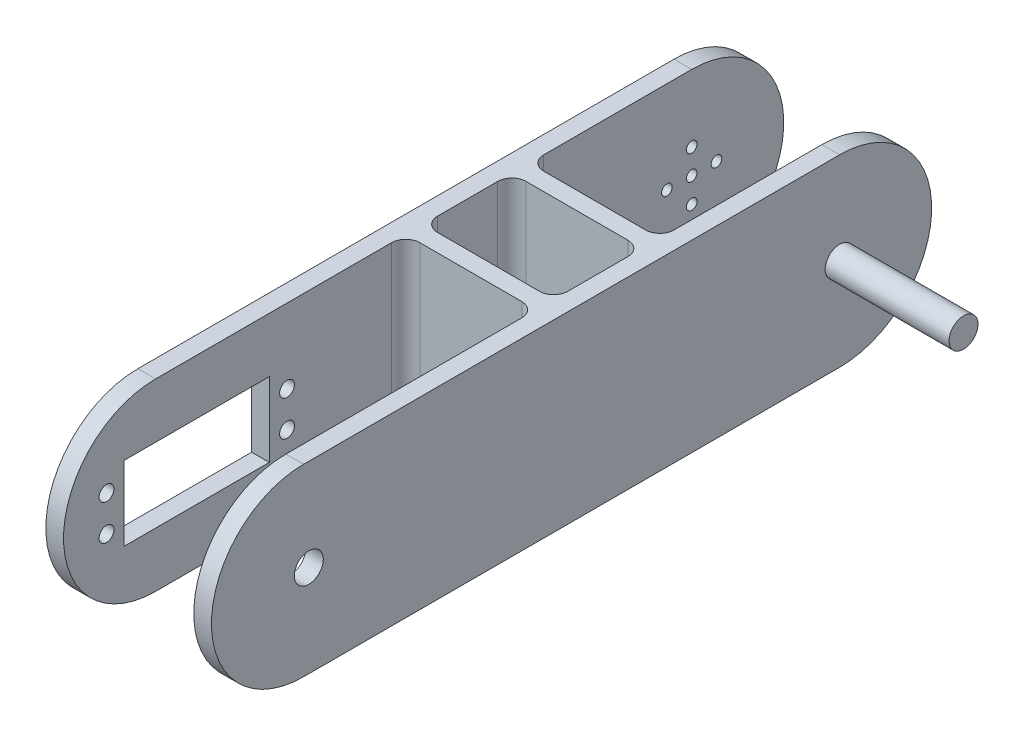
SolidWorks part; units mm, degrees
ref_plane "Front Plane" through (0, 0, 0) normal (0, 0, 1) x (1, 0, 0)
ref_plane "Top Plane" through (0, 0, 0) normal (0, 1, 0) x (1, 0, 0)
ref_plane "Right Plane" through (0, 0, 0) normal (1, 0, 0) x (0, 0, -1)
sketch "Sketch3" plane through (0, 0, 0) normal (1, 0, 0) x (0, 0, -1)
  line L0 (-75.75, 0) -> (75.75, 0) construction
  line L1 (-75.75, 26) -> (75.75, 26)
  line L2 (-75.75, -26) -> (75.75, -26)
  arc A0 (-75.75, 26) -> (-75.75, -26) centre (-75.75, 0) ccw
  arc A1 (75.75, -26) -> (75.75, 26) centre (75.75, 0) ccw
  point P2 (0, 0)
  dimension "D1" = 151.5
  dimension "D2" = 52
extrude "Boss-Extrude3" add sketch "Sketch3" along normal blind 5
sketch "Sketch4" plane through (0, 0, 0) normal (-1, 0, 0) x (0, 0, 1)
  circle A0 centre (-75.75, 0) radius 1.5
  circle A1 centre (-75.75, 0) radius 7 construction
  circle A2 centre (-75.75, 7) radius 1.5
  circle A3 centre (-68.75, 0) radius 1.5
  circle A4 centre (-75.75, -7) radius 1.5
  circle A5 centre (-82.75, 0) radius 1.5
  point P15 (-75.75, 0)
  dimension "D1" = 3
  dimension "D2" = 14
  dimension "D3" = 3
  dimension "D5" = 14
  dimension "D6" = 7
  dimension "D4" = 4
extrude "Cut-Extrude1" cut sketch "Sketch4" against normal blind 70
sketch "Sketch5" plane through (0, 0, 0) normal (-1, 0, 0) x (0, 0, 1)
  line L0 (0, 0) -> (101.75, 0) construction
  line L1 (43.6, -10.5) -> (84.6, -10.5)
  line L2 (43.6, -10.5) -> (43.6, 10.5)
  line L3 (84.6, -10.5) -> (84.6, 10.5)
  line L4 (43.6, 10.5) -> (84.6, 10.5)
  line L5 (43.6, -10.5) -> (84.6, 10.5) construction
  line L6 (84.6, -10.5) -> (43.6, 10.5) construction
  line L7 (64.1, 0) -> (64.1, -10.5) construction
  arc A0 (75.75, -26) -> (75.75, 26) centre (75.75, 0) ccw construction
  circle A1 centre (89.6, 5) radius 2.1
  circle A2 centre (89.6, -5) radius 2.1
  circle A3 centre (38.6, -5) radius 2.1
  circle A4 centre (38.6, 5) radius 2.1
  point P7 (64.1, 0)
  dimension "D5" = 4.2
  dimension "D6" = 5.5
  dimension "D7" = 5
  dimension "D1" = 41
  dimension "D2" = 21
  dimension "D3" = 43.6
  dimension "D4" = 10.5
extrude "Cut-Extrude2" cut sketch "Sketch5" against normal blind 10
sketch "Sketch6" plane through (5, 0, 0) normal (1, 0, 0) x (0, 0, -1)
  line L0 (75.75, 26) -> (-75.75, 26) construction
  line L1 (29.9316, 26) -> (24.9316, 26)
  line L2 (29.9316, 26) -> (29.9316, -26)
  line L3 (29.9316, -26) -> (24.9316, -26)
  line L4 (24.9316, 26) -> (24.9316, -26)
  line L5 (-75.75, -26) -> (75.75, -26) construction
  line L6 (-0.0684, 26) -> (-0.0684, -26)
  line L7 (-0.0684, 26) -> (-5.0684, 26)
  line L8 (-5.0684, 26) -> (-5.0684, -26)
  line L9 (-0.0684, -26) -> (-5.0684, -26)
  dimension "D1" = 5
  dimension "D2" = 2
extrude "Boss-Extrude4" add sketch "Sketch6" along normal blind 36.8
sketch "Sketch7" plane through (41.8, 0, 0) normal (1, 0, 0) x (0, 0, -1)
  line L0 (-75.75, 26) -> (75.75, 26)
  line L1 (-75.75, -26) -> (75.75, -26)
  arc A0 (-75.75, 26) -> (-75.75, -26) centre (-75.75, 0) ccw
  arc A1 (75.75, 26) -> (75.75, -26) centre (75.75, 0) cw
  dimension "D2" = 52
  dimension "D1" = 2
extrude "Boss-Extrude5" add sketch "Sketch7" along normal blind 5
sketch "Sketch8" plane through (41.8, 0, 0) normal (-1, 0, 0) x (0, 0, 1)
  circle A0 centre (-75.75, 0) radius 4.1
  dimension "D1" = 8.2
extrude "Boss-Extrude6" add sketch "Sketch8" against normal blind 40
sketch "Sketch10" plane through (46.8, 0, 0) normal (1, 0, 0) x (0, 0, -1)
  line L0 (75.75, 26) -> (-75.75, 26) construction
  circle A0 centre (-74.25, 0) radius 4.1
  arc A1 (-75.75, 26) -> (-75.75, -26) centre (-75.75, 0) ccw construction
  dimension "D1" = 8.2
  dimension "D2" = 26
  dimension "D3" = 1.5
extrude "Cut-Extrude5" cut sketch "Sketch10" against normal blind 25
fillet "Fillet2" radius 4 8 edges at (41.8, 0, 0.0684) (5, 0, 0.0684) (5, 0, -24.9316) (41.8, 0, -24.9316) (41.8, 0, 5.0684) (5, 0, 5.0684) (41.8, 0, -29.9316) (5, 0, -29.9316)
